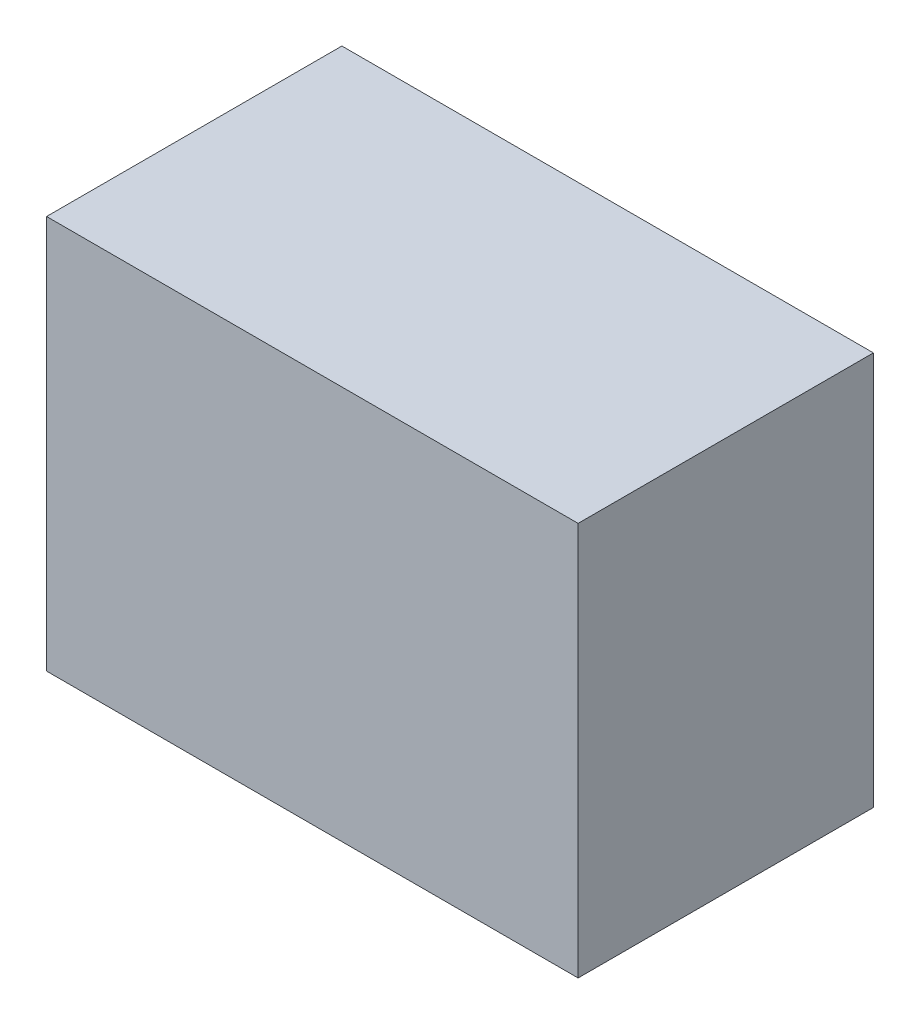
SolidWorks part; units mm, degrees
material "Delrin 2700 NC010, Low Viscosity Acetal Copolymer (SS)"
ref_plane "Front Plane" through (0, 0, 0) normal (0, 0, 1) x (1, 0, 0)
ref_plane "Top Plane" through (0, 0, 0) normal (0, 1, 0) x (1, 0, 0)
ref_plane "Right Plane" through (0, 0, 0) normal (1, 0, 0) x (0, 0, -1)
sketch "Sketch1" plane through (0, -8.2414, 0) normal (0, 1, 0) x (1, 0, 0)
  line L1 (135, 75) -> (-135, 75)
  line L2 (135, 75) -> (135, -75)
  line L3 (135, -75) -> (-135, -75)
  line L4 (-135, 75) -> (-135, -75)
  line L5 (135, 75) -> (-135, -75) construction
  line L6 (135, -75) -> (-135, 75) construction
  point P0 (0, 0)
  dimension "D1" = 150
  dimension "D2" = 270
extrude "Boss-Extrude1" add sketch "Sketch1" along normal blind 200
